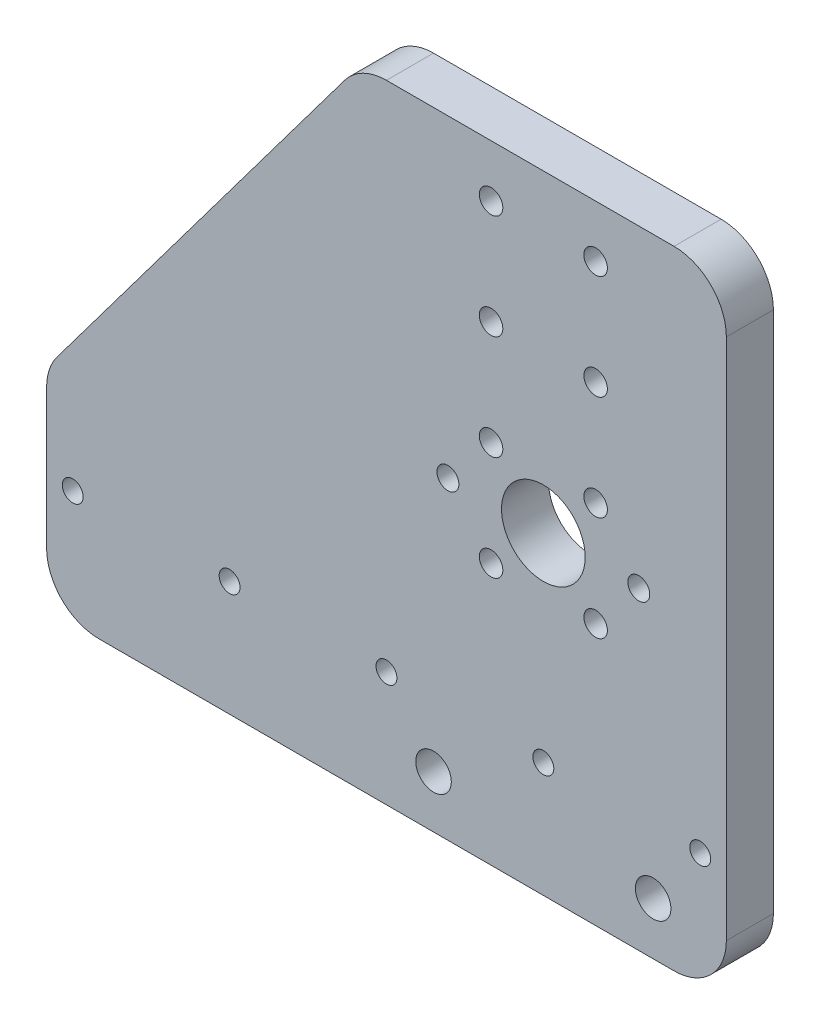
SolidWorks part; units mm, degrees
ref_plane "Front" through (0, 0, 0) normal (0, 0, 1) x (1, 0, 0)
ref_plane "Top" through (0, 0, 0) normal (0, 1, 0) x (1, 0, 0)
ref_plane "Right" through (0, 0, 0) normal (1, 0, 0) x (0, 0, -1)
sketch "Esquisse1" plane through (0, 0, 0) normal (0, 0, 1) x (1, 0, 0)
  line L0 (0, 0) -> (130, 0)
  line L1 (130, 0) -> (130, 120)
  line L2 (130, 120) -> (60, 120)
  line L3 (60, 120) -> (0, 40)
  line L4 (0, 40) -> (0, 0)
  dimension "D1" = 120
  dimension "D2" = 130
  dimension "D3" = 40
  dimension "D4" = 70
extrude "Boss.-Extru.1" add sketch "Esquisse1" along normal blind 9
sketch "Esquisse2" plane through (0, 0, 9) normal (0, 0, 1) x (1, 0, 0)
  line L0 (0, 22) -> (130, 22) construction
  line L1 (0, 40) -> (0, 0) construction
  line L2 (130, 0) -> (130, 120) construction
  line L3 (65, 22) -> (65, 26.8679) construction
  line L4 (0, 0) -> (130, 0) construction
  line L5 (95, 120) -> (95, 80) construction
  line L6 (130, 120) -> (60, 120) construction
  line L7 (95, 100) -> (92.3142, 100) construction
  line L8 (95, 80) -> (85.6936, 80) construction
  line L9 (95, 60) -> (92.3142, 60) construction
  circle A0 centre (65, 22) radius 2
  circle A1 centre (35, 22) radius 2
  circle A2 centre (5, 22) radius 2
  circle A3 centre (125, 22) radius 2
  circle A4 centre (95, 22) radius 2
  circle A5 centre (85, 110) radius 2.25
  circle A6 centre (85, 90) radius 2.25
  circle A7 centre (105, 90) radius 2.25
  circle A8 centre (105, 110) radius 2.25
  circle A9 centre (105, 50) radius 2.25
  circle A10 centre (105, 70) radius 2.25
  circle A11 centre (85, 70) radius 2.25
  circle A12 centre (85, 50) radius 2.25
  dimension "D1" = 4
  dimension "D2" = 30
  dimension "D3" = 30
  dimension "D6" = 20
  dimension "D7" = 10
  dimension "D8" = 4.5
  dimension "D4" = 22
  dimension "D5" = 20
extrude "Enlèv. mat.-Extru.1" cut sketch "Esquisse2" against normal through all
sketch "Esquisse3" plane through (0, 0, 9) normal (0, 0, 1) x (1, 0, 0)
  line L0 (85, 50) -> (105, 70) construction
  line L1 (95, 60) -> (95, 10) construction
  line L2 (95, 10) -> (74, 10) construction
  circle A0 centre (95, 60) radius 8
  circle A1 centre (74, 10) radius 3.4
  circle A2 centre (116, 10) radius 3.4
  dimension "D1" = 16
  dimension "D2" = 21
  dimension "D3" = 6.8
  dimension "D4" = 50
extrude "Enlèv. mat.-Extru.2" cut sketch "Esquisse3" against normal through all
fillet "Congé1" radius 10 5 edges at (0, 40, 4.5) (60, 120, 4.5) (130, 120, 4.5) (130, 0, 4.5) (0, 0, 4.5)
sketch "Esquisse5" [suppressed] plane through (0, 0, 0) normal (0, 0, -1) x (-1, 0, 0)
  line L0 (-95, 60) -> (-95, 81.9203) construction
  line L1 (-95, 60) -> (-116.9203, 60) construction
  line L2 (-95, 60) -> (-91.0893, 63.9107) construction
  line L3 (-95, 60) -> (-95, 38.0797) construction
  line L4 (-95, 60) -> (-73.0797, 60) construction
  circle A0 centre (-95, 81.9203) radius 1.5
  circle A1 centre (-116.9203, 60) radius 1.5
  circle A2 centre (-95, 38.0797) radius 1.5
  circle A3 centre (-73.0797, 60) radius 1.5
  dimension "D1" = 31
  dimension "D2" = 3
  dimension "D3" = 45
extrude "Enlèv. mat.-Extru.3" [suppressed] cut sketch "Esquisse5" against normal through all
sketch "Esquisse6" plane through (0, 0, 0) normal (0, 0, -1) x (-1, 0, 0)
  line L0 (-113.25, 60) -> (-95, 60) construction
  line L1 (-95, 60) -> (-95, 52) construction
  circle A0 centre (-113.25, 60) radius 2.1
  circle A2 centre (-95, 60) radius 8 construction
  circle A3 centre (-76.75, 60) radius 2.1
  dimension "D2" = 4.2
  dimension "D1" = 18.25
extrude "Enlèv. mat.-Extru.4" cut sketch "Esquisse6" against normal through all
